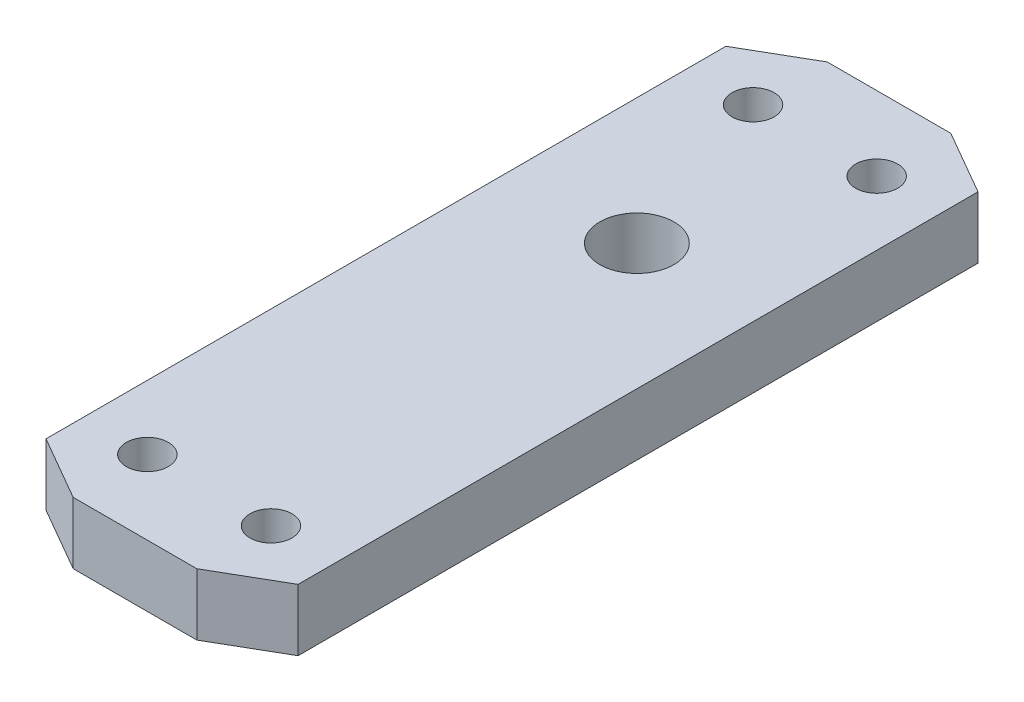
SolidWorks part; units mm, degrees
ref_plane "前视基准面" through (0, 0, 0) normal (0, 0, 1) x (1, 0, 0)
ref_plane "上视基准面" through (0, 0, 0) normal (0, 1, 0) x (1, 0, 0)
ref_plane "右视基准面" through (0, 0, 0) normal (1, 0, 0) x (0, 0, -1)
other "Configuration Table"
sketch "草图1" plane through (0, 0, 0) normal (0, 1, 0) x (1, 0, 0)
  line L0 (2730.3855, 1310.3497) -> (2740.3855, 1310.3497)
  line L1 (2740.3855, 1310.3497) -> (2745.5817, 1307.3497)
  line L2 (2745.5817, 1307.3497) -> (2745.5817, 1252.3497)
  line L3 (2745.5817, 1252.3497) -> (2740.3855, 1249.3497)
  line L4 (2740.3855, 1249.3497) -> (2730.3855, 1249.3497)
  line L5 (2730.3855, 1249.3497) -> (2725.1894, 1252.3497)
  line L6 (2725.1894, 1252.3497) -> (2725.1894, 1307.3497)
  line L7 (2725.1894, 1307.3497) -> (2730.3855, 1310.3497)
  circle A0 centre (2740.3855, 1255.3497) radius 1.7
  circle A1 centre (2730.3855, 1255.3497) radius 1.7
  circle A2 centre (2735.3855, 1289.9497) radius 3
  circle A3 centre (2730.3855, 1304.3497) radius 1.7
  circle A4 centre (2740.3855, 1304.3497) radius 1.7
extrude "凸台-拉伸1" add sketch "草图1" along normal blind 5
